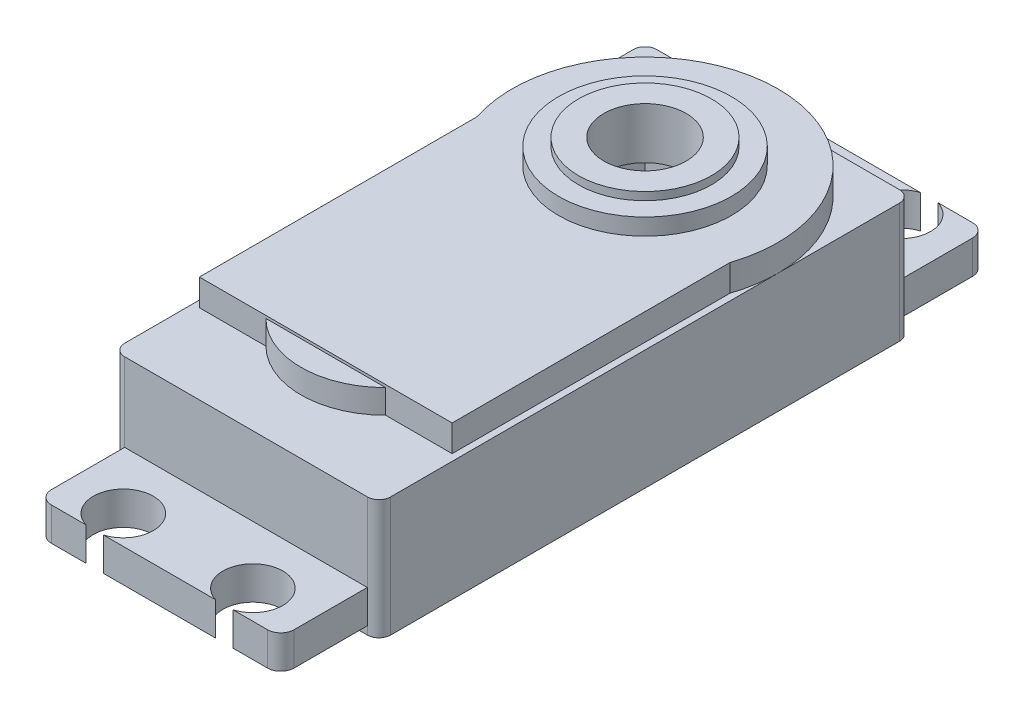
SolidWorks part; units mm, degrees
ref_plane "Front Plane" through (0, 0, 0) normal (0, 0, 1) x (1, 0, 0)
ref_plane "Top Plane" through (0, 0, 0) normal (0, 1, 0) x (1, 0, 0)
ref_plane "Right Plane" through (0, 0, 0) normal (1, 0, 0) x (0, 0, -1)
sketch "Sketch1" plane through (0, 0, 0) normal (0, 1, 0) x (1, 0, 0)
  line L0 (0, 0) -> (4, 0) construction
  line L1 (-9.12, 20) -> (9.12, 20)
  line L2 (-10, 19.12) -> (-10, -19.12)
  line L3 (-9.12, -20) -> (9.12, -20)
  line L4 (10, 19.12) -> (10, -19.12)
  line L5 (-10, 20) -> (10, -20) construction
  line L6 (-10, -20) -> (10, 20) construction
  line L7 (0, 0) -> (0, -4) construction
  arc A0 (-9.12, 20) -> (-10, 19.12) centre (-9.12, 19.12) ccw
  arc A1 (9.12, 20) -> (10, 19.12) centre (9.12, 19.12) cw
  arc A2 (9.12, -20) -> (10, -19.12) centre (9.12, -19.12) ccw
  arc A3 (-9.12, -20) -> (-10, -19.12) centre (-9.12, -19.12) cw
  point P0 (0, 0)
  dimension "D3" = 0.88
  dimension "D5" = 1.76
  dimension "D1" = 20
  dimension "D2" = 40
  dimension "D4" = 0.88
extrude "Boss-Extrude1" add sketch "Sketch1" along normal blind 9
shell "Shell1" thickness 1
sketch "Sketch2" plane through (0, 9, 0) normal (0, 1, 0) x (1, 0, 0)
  line L1 (9.12, 20) -> (-9.12, 20) construction
  line L2 (-10, 19.12) -> (-10, -19.12) construction
  line L3 (9.5, -14) -> (-9.5, -14)
  line L4 (9.5, -14) -> (9.5, 6.8775)
  line L6 (-9.5, -14) -> (-9.5, 6.8775)
  line L7 (9.5, -14) -> (-9.5, 10) construction
  line L8 (9.5, 10) -> (-9.5, -14) construction
  line L9 (10, -19.12) -> (10, 19.12) construction
  line L10 (-9.12, -20) -> (9.12, -20) construction
  arc A1 (9.5, 6.8775) -> (-9.5, 6.8775) centre (0, 10) ccw
  point P4 (0, -2)
  dimension "D2" = 10
  dimension "D3" = 0.5
  dimension "D4" = 0.5
  dimension "D6" = 6
extrude "Boss-Extrude2" add sketch "Sketch2" along normal blind 2
sketch "Sketch3" plane through (0, 11, 0) normal (0, 1, 0) x (1, 0, 0)
  circle A0 centre (0, 10) radius 6.5
  arc A1 (9.5, 6.8775) -> (-9.5, 6.8775) centre (0, 10) ccw construction
  point P5 (0, 20)
  dimension "D1" = 13
  dimension "D2" = 10
extrude "Boss-Extrude3" add sketch "Sketch3" along normal blind 1.25
sketch "Sketch4" plane through (0, 12.25, 0) normal (0, 1, 0) x (1, 0, 0)
  circle A0 centre (0, 10) radius 5
  dimension "D1" = 10
extrude "Boss-Extrude4" add sketch "Sketch4" along normal blind 0.6
sketch "Sketch5" plane through (0, 12.85, 0) normal (0, 1, 0) x (1, 0, 0)
  circle A0 centre (0, 10) radius 3.1
  dimension "D1" = 6.2
extrude "Cut-Extrude1" cut sketch "Sketch5" against normal through all and the other way through all
sketch "Sketch6" plane through (0, 9, 0) normal (0, 1, 0) x (1, 0, 0)
  line L0 (-4.5, -14) -> (4.5, -14)
  line L2 (-9.5, -14) -> (9.5, -14) construction
  arc A0 (-4.5, -14) -> (4.5, -14) centre (0, -9.5) ccw
  point P3 (0, -14)
  dimension "D1" = 9
  dimension "D2" = 9.5
extrude "Boss-Extrude5" add sketch "Sketch6" along normal blind 1.8
ref_plane "Plane1" through (0, 0.6, 0) normal (0, 1, 0) x (1, 0, 0)
sketch "Sketch7" plane through (0, 0.6, 0) normal (0, 1, 0) x (1, 0, 0)
  line L0 (-9.12, 20) -> (-9.12, 26.5)
  line L1 (0, 20) -> (-9.12, 20) construction
  line L2 (-9.12, 26.5) -> (9.12, 26.5)
  line L3 (9.12, 26.5) -> (9.12, 20)
  line L4 (9.12, 20) -> (0, 20) construction
  line L5 (9.12, 20) -> (-9.12, 20)
  line L6 (-10, 19.12) -> (-10, 10) construction
  line L7 (10, 10) -> (10, 19.12) construction
  line L8 (9.12, -20) -> (9.12, -26.5)
  line L9 (-9.12, -20) -> (9.12, -20) construction
  line L10 (9.12, -26.5) -> (-9.12, -26.5)
  line L11 (-9.12, -26.5) -> (-9.12, -20)
  line L12 (-9.12, -20) -> (9.12, -20)
  line L14 (-10, 10) -> (-10, -19.12) construction
  line L15 (10, -19.12) -> (10, 10) construction
  dimension "D6" = 0.88
  dimension "D1" = 0.88
  dimension "D2" = 0.88
  dimension "D3" = 6.5
  dimension "D4" = 6.5
  dimension "D5" = 0.88
extrude "Boss-Extrude6" add sketch "Sketch7" along normal blind 2.5
sketch "Sketch8" plane through (0, 3.1, 0) normal (0, 1, 0) x (1, 0, 0)
  line L0 (-9.12, 20) -> (9.12, 20) construction
  line L1 (-9.12, 26.5) -> (-9.12, 20) construction
  line L2 (9.12, 20) -> (9.12, 26.5) construction
  line L3 (-9.12, -20) -> (-9.12, -26.5) construction
  line L4 (9.12, -26.5) -> (9.12, -20) construction
  line L5 (-9.12, -20) -> (9.12, -20) construction
  line L6 (9.12, -20) -> (-9.12, -20) construction
  circle A0 centre (-4.87, 24.35) radius 2.25
  circle A1 centre (4.87, 24.35) radius 2.25
  circle A2 centre (-4.87, -24.35) radius 2.25
  circle A3 centre (4.87, -24.35) radius 2.25
  point P6 (0, 20)
  dimension "D1" = 4.5
  dimension "D6" = 4.5
  dimension "D2" = 4.35
  dimension "D3" = 4.35
  dimension "D4" = 4.25
  dimension "D5" = 4.25
  dimension "D7" = 4.25
  dimension "D8" = 4.25
  dimension "D9" = 4.35
  dimension "D10" = 4.35
extrude "Cut-Extrude2" cut sketch "Sketch8" against normal up to next
fillet "Fillet2" radius 1 4 edges at (-9.12, 1.85, 26.5) (9.12, 1.85, 26.5) (9.12, 1.85, -26.5) (-9.12, 1.85, -26.5)
sketch "Sketch9" plane through (0, 8, 0) normal (0, -1, 0) x (1, 0, 0)
  circle A0 centre (0, -10) radius 9
  dimension "D1" = 18
extrude "Cut-Extrude3" cut sketch "Sketch9" against normal blind 1 and the other way through all
